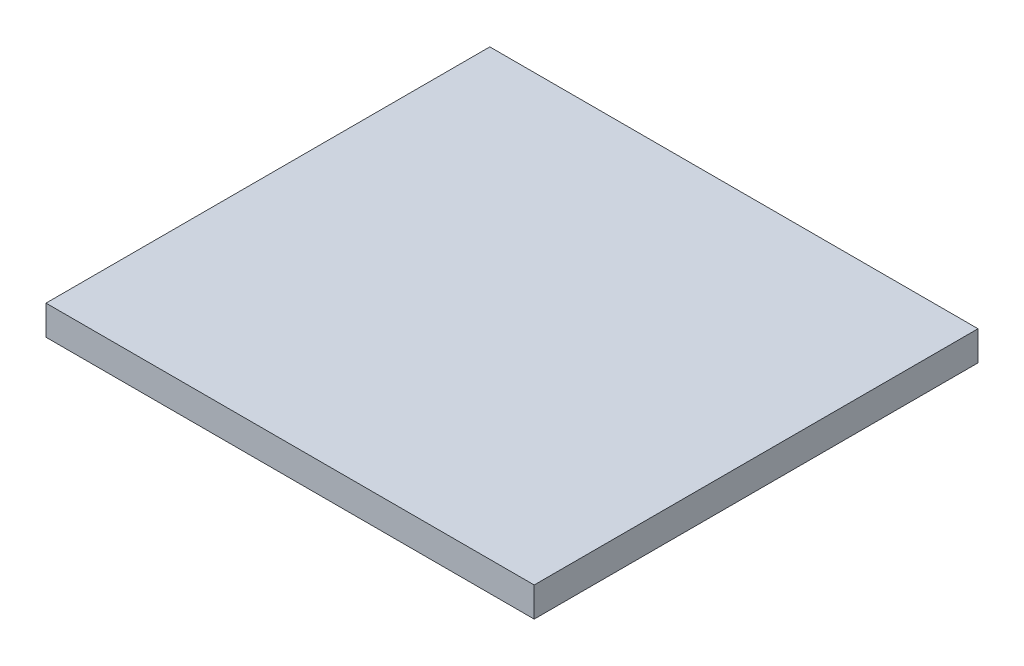
SolidWorks part; units mm, degrees
material "Plywood"
ref_plane "Front Plane" through (0, 0, 0) normal (0, 0, 1) x (1, 0, 0)
ref_plane "Top Plane" through (0, 0, 0) normal (0, 1, 0) x (1, 0, 0)
ref_plane "Right Plane" through (0, 0, 0) normal (1, 0, 0) x (0, 0, -1)
sketch "Sketch1" plane through (0, 0, 0) normal (0, 1, 0) x (1, 0, 0)
  line L1 (-82.5, -75) -> (82.5, -75)
  line L2 (-82.5, -75) -> (-82.5, 75)
  line L3 (-82.5, 75) -> (82.5, 75)
  line L4 (82.5, -75) -> (82.5, 75)
  line L5 (-82.5, -75) -> (82.5, 75) construction
  line L6 (-82.5, 75) -> (82.5, -75) construction
  point P0 (0, 0)
  dimension "D1" = 150
  dimension "D2" = 165
extrude "Boss-Extrude1" add sketch "Sketch1" along normal mid plane 10
